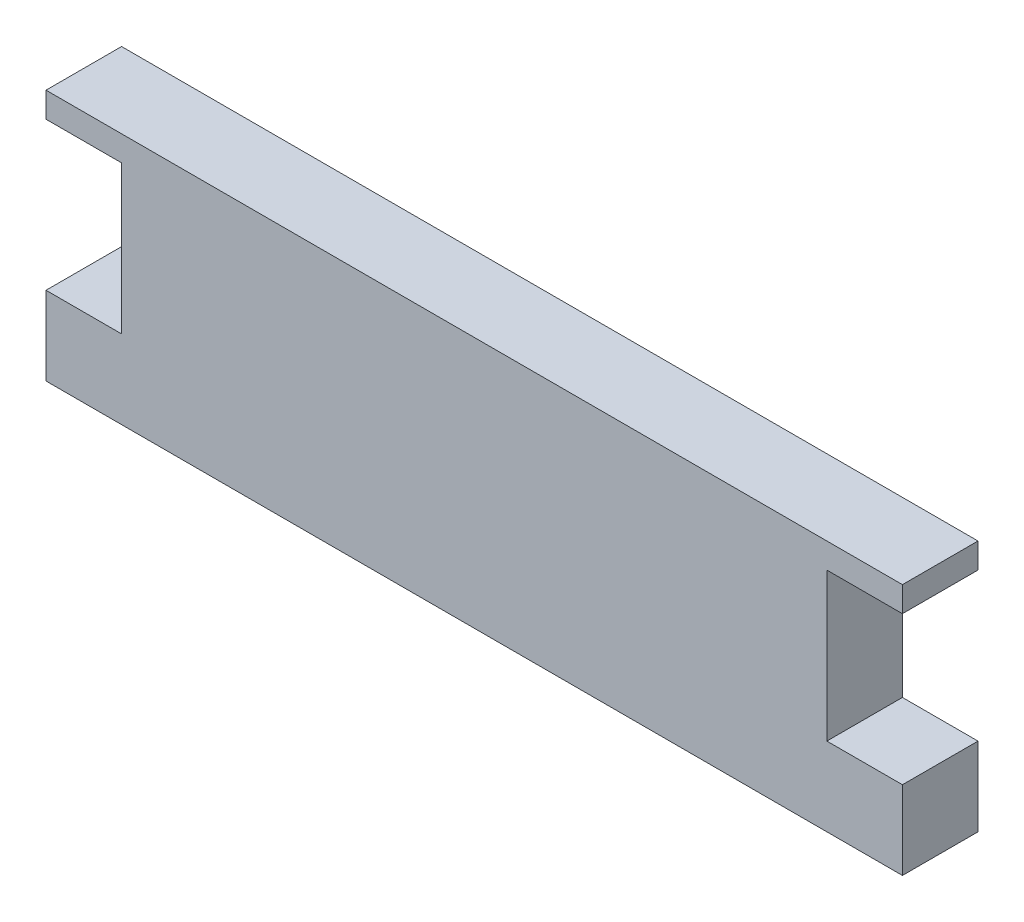
SolidWorks part; units mm, degrees
ref_plane "Front Plane" through (0, 0, 0) normal (0, 0, 1) x (1, 0, 0)
ref_plane "Top Plane" through (0, 0, 0) normal (0, 1, 0) x (1, 0, 0)
ref_plane "Right Plane" through (0, 0, 0) normal (1, 0, 0) x (0, 0, -1)
sketch "Sketch1" plane through (0, 0, 0) normal (0, 0, 1) x (1, 0, 0)
  line L0 (-43.4426, -17.0825) -> (-43.4426, -32.6844)
  line L1 (-43.4426, 17.3156) -> (126.5574, 17.3156)
  line L2 (-43.4426, 17.3156) -> (-43.4426, 12.3155)
  line L3 (-43.4426, -32.6844) -> (126.5574, -32.6844)
  line L4 (126.5574, 17.3156) -> (126.5574, 12.3155)
  line L5 (-43.4426, 12.3155) -> (-28.4426, 12.3155)
  line L6 (41.5574, 17.3156) -> (41.5574, -36.0794) construction
  line L7 (-43.4426, -17.0825) -> (-28.4426, -17.0825)
  line L8 (-28.4426, 12.3155) -> (-28.4426, -17.0825)
  line L9 (126.5574, -17.0825) -> (111.5574, -17.0825)
  line L10 (111.5574, 12.3155) -> (111.5574, -17.0825)
  line L11 (126.5574, 12.3155) -> (111.5574, 12.3155)
  line L12 (126.5574, -17.0825) -> (126.5574, -32.6844)
  point P15 (126.5574, -17.0825)
  dimension "D1" = 50
  dimension "D2" = 170
  dimension "D3" = 15
extrude "Boss-Extrude1" add sketch "Sketch1" along normal blind 15
